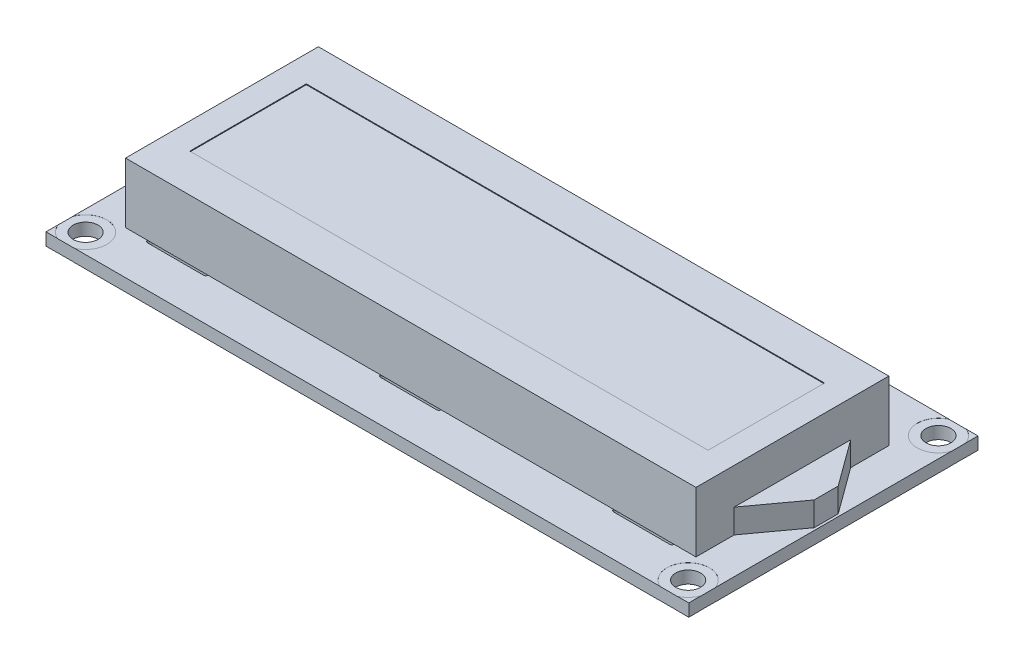
SolidWorks part; units mm, degrees
ref_plane "Front Plane" through (0, 0, 0) normal (0, 0, 1) x (1, 0, 0)
ref_plane "Top Plane" through (0, 0, 0) normal (0, 1, 0) x (1, 0, 0)
ref_plane "Right Plane" through (0, 0, 0) normal (1, 0, 0) x (0, 0, -1)
sketch "Sketch1" plane through (0, 0, 0) normal (0, 1, 0) x (1, 0, 0)
  line L1 (-40, -18) -> (40, -18)
  line L2 (-40, -18) -> (-40, 18)
  line L3 (-40, 18) -> (40, 18)
  line L4 (40, -18) -> (40, 18)
  line L5 (-40, -18) -> (40, 18) construction
  line L6 (-40, 18) -> (40, -18) construction
  point P0 (0, 0)
  dimension "D1" = 36
  dimension "D2" = 80
extrude "PCB" add sketch "Sketch1" along normal blind 1.55
sketch "Sketch2" plane through (0, 1.55, 0) normal (0, 1, 0) x (1, 0, 0)
  line L0 (-42.4796, 0) -> (42.3992, 0) construction
  line L1 (-37.5, 15.575) -> (37.5, 15.575) construction
  circle A0 centre (-37.5, 15.575) radius 1.55
  circle A1 centre (37.5, 15.575) radius 1.55
  circle A2 centre (37.5, -15.575) radius 1.55
  circle A3 centre (-37.5, -15.575) radius 1.55
  circle A4 centre (-37.5, 15.575) radius 2.6 construction
  point P12 (0, 15.575)
  dimension "D1" = 3.1
  dimension "D4" = 5.2
  dimension "D2" = 75
  dimension "D3" = 15.575
extrude "MountingHoles" cut sketch "Sketch2" against normal through all
sketch "Sketch3" plane through (0, 1.55, 0) normal (0, 1, 0) x (1, 0, 0)
  line L0 (0, -21.8483) -> (0, 21.8483) construction
  line L1 (-44.6988, 0) -> (43.4961, 0) construction
  line L2 (40, 18) -> (-40, 18) construction
  line L3 (-32.9, 18) -> (-31.1, 18)
  line L4 (-32.9, 18) -> (-32.9, 16)
  line L5 (-30.36, 18) -> (-30.36, 16)
  line L6 (-31.1, 18) -> (-31.1, 16)
  line L7 (-30.36, 18) -> (-28.56, 18)
  line L8 (-28.56, 18) -> (-28.56, 16)
  line L9 (-27.82, 18) -> (-27.82, 16)
  line L10 (-27.82, 18) -> (-26.02, 18)
  line L11 (-26.02, 18) -> (-26.02, 16)
  line L12 (-25.28, 18) -> (-25.28, 16)
  line L13 (-25.28, 18) -> (-23.48, 18)
  line L14 (-23.48, 18) -> (-23.48, 16)
  line L15 (-22.74, 18) -> (-22.74, 16)
  line L16 (-22.74, 18) -> (-20.94, 18)
  line L17 (-20.94, 18) -> (-20.94, 16)
  line L18 (-20.2, 18) -> (-20.2, 16)
  line L19 (-20.2, 18) -> (-18.4, 18)
  line L20 (-18.4, 18) -> (-18.4, 16)
  line L21 (-17.66, 18) -> (-17.66, 16)
  line L22 (-17.66, 18) -> (-15.86, 18)
  line L23 (-15.86, 18) -> (-15.86, 16)
  line L24 (-15.12, 18) -> (-15.12, 16)
  line L25 (-15.12, 18) -> (-13.32, 18)
  line L26 (-13.32, 18) -> (-13.32, 16)
  line L27 (-12.58, 18) -> (-12.58, 16)
  line L28 (-12.58, 18) -> (-10.78, 18)
  line L29 (-10.78, 18) -> (-10.78, 16)
  line L30 (-10.04, 18) -> (-10.04, 16)
  line L31 (-10.04, 18) -> (-8.24, 18)
  line L32 (-8.24, 18) -> (-8.24, 16)
  line L33 (-7.5, 18) -> (-7.5, 16)
  line L34 (-7.5, 18) -> (-5.7, 18)
  line L35 (-5.7, 18) -> (-5.7, 16)
  line L36 (-4.96, 18) -> (-4.96, 16)
  line L37 (-4.96, 18) -> (-3.16, 18)
  line L38 (-3.16, 18) -> (-3.16, 16)
  line L39 (-2.42, 18) -> (-2.42, 16)
  line L40 (-2.42, 18) -> (-0.62, 18)
  line L41 (-0.62, 18) -> (-0.62, 16)
  line L42 (0.12, 18) -> (0.12, 16)
  line L43 (0.12, 18) -> (1.92, 18)
  line L44 (1.92, 18) -> (1.92, 16)
  line L45 (2.66, 18) -> (2.66, 16)
  line L46 (2.66, 18) -> (4.46, 18)
  line L47 (4.46, 18) -> (4.46, 16)
  line L48 (5.2, 18) -> (5.2, 16)
  line L49 (5.2, 18) -> (7, 18)
  line L50 (7, 18) -> (7, 16)
  circle A0 centre (-37.5, 15.575) radius 2.65
  circle A1 centre (37.5, 15.575) radius 2.65
  circle A2 centre (37.5, -15.575) radius 2.65
  circle A3 centre (-37.5, -15.575) radius 2.65
  arc A4 (-32.9, 16) -> (-31.1, 16) centre (-32, 16) ccw
  arc A5 (-30.36, 16) -> (-28.56, 16) centre (-29.46, 16) ccw
  arc A6 (-27.82, 16) -> (-26.02, 16) centre (-26.92, 16) ccw
  arc A7 (-25.28, 16) -> (-23.48, 16) centre (-24.38, 16) ccw
  arc A8 (-22.74, 16) -> (-20.94, 16) centre (-21.84, 16) ccw
  arc A9 (-20.2, 16) -> (-18.4, 16) centre (-19.3, 16) ccw
  arc A10 (-17.66, 16) -> (-15.86, 16) centre (-16.76, 16) ccw
  arc A11 (-15.12, 16) -> (-13.32, 16) centre (-14.22, 16) ccw
  arc A12 (-12.58, 16) -> (-10.78, 16) centre (-11.68, 16) ccw
  arc A13 (-10.04, 16) -> (-8.24, 16) centre (-9.14, 16) ccw
  arc A14 (-7.5, 16) -> (-5.7, 16) centre (-6.6, 16) ccw
  arc A15 (-4.96, 16) -> (-3.16, 16) centre (-4.06, 16) ccw
  arc A16 (-2.42, 16) -> (-0.62, 16) centre (-1.52, 16) ccw
  arc A17 (0.12, 16) -> (1.92, 16) centre (1.02, 16) ccw
  arc A18 (2.66, 16) -> (4.46, 16) centre (3.56, 16) ccw
  arc A19 (5.2, 16) -> (7, 16) centre (6.1, 16) ccw
  point P21 (0, 0)
  dimension "D1" = 5.3
  dimension "D2" = 1.8
  dimension "D3" = 5.5
  dimension "D4" = 2
  dimension "D6" = 2.54
  dimension "D5" = 16
extrude "Pads" cut sketch "Sketch3" against normal blind 0.01
sketch "Sketch4" plane through (0, 1.55, 0) normal (0, 1, 0) x (1, 0, 0)
  circle A0 centre (-32, 16) radius 0.5
  circle A1 centre (-29.46, 16) radius 0.5
  circle A2 centre (-26.92, 16) radius 0.5
  circle A3 centre (-24.38, 16) radius 0.5
  circle A4 centre (-21.84, 16) radius 0.5
  circle A5 centre (-19.3, 16) radius 0.5
  circle A6 centre (-16.76, 16) radius 0.5
  circle A7 centre (-14.22, 16) radius 0.5
  circle A8 centre (-11.68, 16) radius 0.5
  circle A9 centre (-9.14, 16) radius 0.5
  circle A10 centre (-6.6, 16) radius 0.5
  circle A11 centre (-4.06, 16) radius 0.5
  circle A12 centre (-1.52, 16) radius 0.5
  circle A13 centre (1.02, 16) radius 0.5
  circle A14 centre (3.56, 16) radius 0.5
  circle A15 centre (6.1, 16) radius 0.5
  dimension "D1" = 1
  dimension "D2" = 16
extrude "ConnecterHoles" cut sketch "Sketch4" against normal through all
sketch "Sketch5" plane through (0, 1.55, 0) normal (0, 1, 0) x (1, 0, 0)
  line L0 (36.4314, 18) -> (7, 18) construction
  line L1 (-35.5, -12.6) -> (35.5, -12.6)
  line L2 (-35.5, -12.6) -> (-35.5, 11.4)
  line L3 (-35.5, 11.4) -> (35.5, 11.4)
  line L4 (35.5, -12.6) -> (35.5, 11.4)
  line L5 (-35.5, -12.6) -> (35.5, 11.4) construction
  line L6 (-35.5, 11.4) -> (35.5, -12.6) construction
  point P0 (0, -0.6)
  dimension "D1" = 24
  dimension "D2" = 71
  dimension "D3" = 6.6
extrude "PanelBody" add sketch "Sketch5" along normal blind 7.5
sketch "Sketch6" plane through (0, 9.05, 0) normal (0, 1, 0) x (1, 0, 0)
  line L0 (35.5, -0.6) -> (-35.5, -0.6) construction
  line L1 (-32.25, -7.85) -> (32.25, -7.85)
  line L2 (-32.25, -7.85) -> (-32.25, 6.65)
  line L3 (-32.25, 6.65) -> (32.25, 6.65)
  line L4 (32.25, -7.85) -> (32.25, 6.65)
  line L5 (-32.25, -7.85) -> (32.25, 6.65) construction
  line L6 (-32.25, 6.65) -> (32.25, -7.85) construction
  line L7 (35.5, -12.6) -> (35.5, 11.4) construction
  line L8 (-35.5, 11.4) -> (-35.5, -12.6) construction
  point P0 (0, -0.6)
  dimension "D1" = 14.5
  dimension "D2" = 64.5
extrude "Screen" cut sketch "Sketch6" against normal blind 0.1
sketch "Sketch7" plane through (0, 1.55, 0) normal (0, 1, 0) x (1, 0, 0)
  line L0 (32.5, 11.4) -> (25.5, 11.4) construction
  line L1 (35.5, 11.4) -> (-35.5, 11.4) construction
  line L2 (35.5, 11.4) -> (-35.5, 11.4) construction
  line L3 (32.5, 11.1258) -> (25.5, 11.1258)
  line L4 (32.5, 11.6742) -> (25.5, 11.6742)
  line L5 (35.5, -12.6) -> (35.5, 11.4) construction
  line L6 (0, 21.7861) -> (0, -23.625) construction
  line L7 (-32.5, 11.4) -> (-25.5, 11.4) construction
  line L8 (-32.5, 11.1258) -> (-25.5, 11.1258)
  line L9 (-32.5, 11.6742) -> (-25.5, 11.6742)
  line L10 (-35.5, -0.6) -> (35.5, -0.6) construction
  line L11 (3.5, 11.4) -> (-3.5, 11.4) construction
  line L12 (3.5, 11.1258) -> (-3.5, 11.1258)
  line L13 (3.5, 11.6742) -> (-3.5, 11.6742)
  line L14 (-32.5, 11.4) -> (-25.5, 11.4) construction
  line L15 (-32.5, 11.1258) -> (-25.5, 11.1258)
  line L16 (-32.5, 11.6742) -> (-25.5, 11.6742)
  line L17 (32.5, 11.4) -> (25.5, 11.4) construction
  line L18 (32.5, 11.1258) -> (25.5, 11.1258)
  line L19 (32.5, 11.6742) -> (25.5, 11.6742)
  line L20 (-32.5, 11.4) -> (-25.5, 11.4) construction
  line L21 (-32.5, 11.1258) -> (-25.5, 11.1258)
  line L22 (-32.5, 11.6742) -> (-25.5, 11.6742)
  line L23 (32.5, 11.4) -> (25.5, 11.4) construction
  line L24 (32.5, 11.1258) -> (25.5, 11.1258)
  line L25 (32.5, 11.6742) -> (25.5, 11.6742)
  line L26 (32.5, 11.4) -> (25.5, 11.4) construction
  line L27 (32.5, 11.1258) -> (25.5, 11.1258)
  line L28 (32.5, 11.6742) -> (25.5, 11.6742)
  line L29 (-32.5, 11.4) -> (-25.5, 11.4) construction
  line L30 (-32.5, 11.1258) -> (-25.5, 11.1258)
  line L31 (-32.5, 11.6742) -> (-25.5, 11.6742)
  line L32 (-35.5, 11.4) -> (-35.5, -12.6) construction
  line L33 (-32.5, 11.4) -> (-25.5, 11.4) construction
  line L34 (-32.5, 11.1258) -> (-25.5, 11.1258)
  line L35 (-32.5, 11.6742) -> (-25.5, 11.6742)
  line L36 (32.5, 11.4) -> (25.5, 11.4) construction
  line L37 (32.5, 11.1258) -> (25.5, 11.1258)
  line L38 (32.5, 11.6742) -> (25.5, 11.6742)
  line L39 (32.5, 11.4) -> (25.5, 11.4) construction
  line L40 (32.5, 11.1258) -> (25.5, 11.1258)
  line L41 (32.5, 11.6742) -> (25.5, 11.6742)
  line L42 (-32.5, 11.4) -> (-25.5, 11.4) construction
  line L43 (-32.5, 11.1258) -> (-25.5, 11.1258)
  line L44 (-32.5, 11.6742) -> (-25.5, 11.6742)
  line L45 (32.5, 11.4) -> (25.5, 11.4) construction
  line L46 (32.5, 11.1258) -> (25.5, 11.1258)
  line L47 (32.5, 11.6742) -> (25.5, 11.6742)
  line L48 (-32.5, 11.4) -> (-25.5, 11.4) construction
  line L49 (-32.5, 11.1258) -> (-25.5, 11.1258)
  line L50 (-32.5, 11.6742) -> (-25.5, 11.6742)
  line L51 (-32.5, 11.4) -> (-25.5, 11.4) construction
  line L52 (-32.5, 11.1258) -> (-25.5, 11.1258)
  line L53 (-32.5, 11.6742) -> (-25.5, 11.6742)
  line L54 (32.5, 11.4) -> (25.5, 11.4) construction
  line L55 (32.5, 11.1258) -> (25.5, 11.1258)
  line L56 (32.5, 11.6742) -> (25.5, 11.6742)
  line L57 (-32.5, 11.4) -> (-25.5, 11.4) construction
  line L58 (-32.5, 11.1258) -> (-25.5, 11.1258)
  line L59 (-32.5, 11.6742) -> (-25.5, 11.6742)
  line L60 (32.5, 11.4) -> (25.5, 11.4) construction
  line L61 (32.5, 11.1258) -> (25.5, 11.1258)
  line L62 (32.5, 11.6742) -> (25.5, 11.6742)
  line L63 (32.5, 11.4) -> (25.5, 11.4) construction
  line L64 (32.5, 11.1258) -> (25.5, 11.1258)
  line L65 (32.5, 11.6742) -> (25.5, 11.6742)
  line L66 (-32.5, 11.4) -> (-25.5, 11.4) construction
  line L67 (-32.5, 11.1258) -> (-25.5, 11.1258)
  line L68 (-32.5, 11.6742) -> (-25.5, 11.6742)
  line L69 (32.5, 11.4) -> (25.5, 11.4) construction
  line L70 (32.5, 11.1258) -> (25.5, 11.1258)
  line L71 (32.5, 11.6742) -> (25.5, 11.6742)
  line L72 (-32.5, 11.4) -> (-25.5, 11.4) construction
  line L73 (-32.5, 11.1258) -> (-25.5, 11.1258)
  line L74 (-32.5, 11.6742) -> (-25.5, 11.6742)
  line L75 (-32.5, 11.4) -> (-25.5, 11.4) construction
  line L76 (-32.5, 11.1258) -> (-25.5, 11.1258)
  line L77 (-32.5, 11.6742) -> (-25.5, 11.6742)
  line L78 (32.5, 11.4) -> (25.5, 11.4) construction
  line L79 (32.5, 11.1258) -> (25.5, 11.1258)
  line L80 (32.5, 11.6742) -> (25.5, 11.6742)
  line L81 (32.5, 11.4) -> (25.5, 11.4) construction
  line L82 (32.5, 11.1258) -> (25.5, 11.1258)
  line L83 (32.5, 11.6742) -> (25.5, 11.6742)
  line L84 (-32.5, 11.4) -> (-25.5, 11.4) construction
  line L85 (-32.5, 11.1258) -> (-25.5, 11.1258)
  line L86 (-32.5, 11.6742) -> (-25.5, 11.6742)
  line L87 (-32.5, 11.4) -> (-25.5, 11.4) construction
  line L88 (-32.5, 11.1258) -> (-25.5, 11.1258)
  line L89 (-32.5, 11.6742) -> (-25.5, 11.6742)
  line L90 (32.5, 11.4) -> (25.5, 11.4) construction
  line L91 (32.5, 11.1258) -> (25.5, 11.1258)
  line L92 (32.5, 11.6742) -> (25.5, 11.6742)
  line L93 (-32.5, 11.4) -> (-25.5, 11.4) construction
  line L94 (-32.5, 11.1258) -> (-25.5, 11.1258)
  line L95 (-32.5, 11.6742) -> (-25.5, 11.6742)
  line L96 (32.5, 11.4) -> (25.5, 11.4) construction
  line L97 (32.5, 11.1258) -> (25.5, 11.1258)
  line L98 (32.5, 11.6742) -> (25.5, 11.6742)
  line L99 (32.5, 11.4) -> (25.5, 11.4) construction
  line L100 (32.5, 11.1258) -> (25.5, 11.1258)
  line L101 (32.5, 11.6742) -> (25.5, 11.6742)
  line L102 (-32.5, 11.4) -> (-25.5, 11.4) construction
  line L103 (-32.5, 11.1258) -> (-25.5, 11.1258)
  line L104 (-32.5, 11.6742) -> (-25.5, 11.6742)
  line L105 (32.5, -12.6) -> (25.5, -12.6) construction
  line L106 (32.5, -12.3258) -> (25.5, -12.3258)
  line L107 (32.5, -12.8742) -> (25.5, -12.8742)
  line L108 (-32.5, -12.6) -> (-25.5, -12.6) construction
  line L109 (-32.5, -12.3258) -> (-25.5, -12.3258)
  line L110 (-32.5, -12.8742) -> (-25.5, -12.8742)
  line L111 (32.5, -12.6) -> (25.5, -12.6) construction
  line L112 (32.5, -12.3258) -> (25.5, -12.3258)
  line L113 (32.5, -12.8742) -> (25.5, -12.8742)
  line L114 (-32.5, -12.6) -> (-25.5, -12.6) construction
  line L115 (-32.5, -12.3258) -> (-25.5, -12.3258)
  line L116 (-32.5, -12.8742) -> (-25.5, -12.8742)
  line L117 (-32.5, -12.6) -> (-25.5, -12.6) construction
  line L118 (-32.5, -12.3258) -> (-25.5, -12.3258)
  line L119 (-32.5, -12.8742) -> (-25.5, -12.8742)
  line L120 (32.5, -12.6) -> (25.5, -12.6) construction
  line L121 (32.5, -12.3258) -> (25.5, -12.3258)
  line L122 (32.5, -12.8742) -> (25.5, -12.8742)
  line L123 (32.5, -12.6) -> (25.5, -12.6) construction
  line L124 (32.5, -12.3258) -> (25.5, -12.3258)
  line L125 (32.5, -12.8742) -> (25.5, -12.8742)
  line L126 (-32.5, -12.6) -> (-25.5, -12.6) construction
  line L127 (-32.5, -12.3258) -> (-25.5, -12.3258)
  line L128 (-32.5, -12.8742) -> (-25.5, -12.8742)
  line L129 (-32.5, -12.6) -> (-25.5, -12.6) construction
  line L130 (-32.5, -12.3258) -> (-25.5, -12.3258)
  line L131 (-32.5, -12.8742) -> (-25.5, -12.8742)
  line L132 (32.5, -12.6) -> (25.5, -12.6) construction
  line L133 (32.5, -12.3258) -> (25.5, -12.3258)
  line L134 (32.5, -12.8742) -> (25.5, -12.8742)
  line L135 (-32.5, -12.6) -> (-25.5, -12.6) construction
  line L136 (-32.5, -12.3258) -> (-25.5, -12.3258)
  line L137 (-32.5, -12.8742) -> (-25.5, -12.8742)
  line L138 (32.5, -12.6) -> (25.5, -12.6) construction
  line L139 (32.5, -12.3258) -> (25.5, -12.3258)
  line L140 (32.5, -12.8742) -> (25.5, -12.8742)
  line L141 (32.5, -12.6) -> (25.5, -12.6) construction
  line L142 (32.5, -12.3258) -> (25.5, -12.3258)
  line L143 (32.5, -12.8742) -> (25.5, -12.8742)
  line L144 (-32.5, -12.6) -> (-25.5, -12.6) construction
  line L145 (-32.5, -12.3258) -> (-25.5, -12.3258)
  line L146 (-32.5, -12.8742) -> (-25.5, -12.8742)
  line L147 (32.5, -12.6) -> (25.5, -12.6) construction
  line L148 (32.5, -12.3258) -> (25.5, -12.3258)
  line L149 (32.5, -12.8742) -> (25.5, -12.8742)
  line L150 (-32.5, -12.6) -> (-25.5, -12.6) construction
  line L151 (-32.5, -12.3258) -> (-25.5, -12.3258)
  line L152 (-32.5, -12.8742) -> (-25.5, -12.8742)
  line L153 (-32.5, -12.6) -> (-25.5, -12.6) construction
  line L154 (-32.5, -12.3258) -> (-25.5, -12.3258)
  line L155 (-32.5, -12.8742) -> (-25.5, -12.8742)
  line L156 (32.5, -12.6) -> (25.5, -12.6) construction
  line L157 (32.5, -12.3258) -> (25.5, -12.3258)
  line L158 (32.5, -12.8742) -> (25.5, -12.8742)
  line L159 (-32.5, -12.6) -> (-25.5, -12.6) construction
  line L160 (-32.5, -12.3258) -> (-25.5, -12.3258)
  line L161 (-32.5, -12.8742) -> (-25.5, -12.8742)
  line L162 (32.5, -12.6) -> (25.5, -12.6) construction
  line L163 (32.5, -12.3258) -> (25.5, -12.3258)
  line L164 (32.5, -12.8742) -> (25.5, -12.8742)
  line L165 (32.5, -12.6) -> (25.5, -12.6) construction
  line L166 (32.5, -12.3258) -> (25.5, -12.3258)
  line L167 (32.5, -12.8742) -> (25.5, -12.8742)
  line L168 (-32.5, -12.6) -> (-25.5, -12.6) construction
  line L169 (-32.5, -12.3258) -> (-25.5, -12.3258)
  line L170 (-32.5, -12.8742) -> (-25.5, -12.8742)
  line L171 (-32.5, -12.6) -> (-25.5, -12.6) construction
  line L172 (-32.5, -12.3258) -> (-25.5, -12.3258)
  line L173 (-32.5, -12.8742) -> (-25.5, -12.8742)
  line L174 (32.5, -12.6) -> (25.5, -12.6) construction
  line L175 (32.5, -12.3258) -> (25.5, -12.3258)
  line L176 (32.5, -12.8742) -> (25.5, -12.8742)
  line L177 (32.5, -12.6) -> (25.5, -12.6) construction
  line L178 (32.5, -12.3258) -> (25.5, -12.3258)
  line L179 (32.5, -12.8742) -> (25.5, -12.8742)
  line L180 (-32.5, -12.6) -> (-25.5, -12.6) construction
  line L181 (-32.5, -12.3258) -> (-25.5, -12.3258)
  line L182 (-32.5, -12.8742) -> (-25.5, -12.8742)
  line L183 (32.5, -12.6) -> (25.5, -12.6) construction
  line L184 (32.5, -12.3258) -> (25.5, -12.3258)
  line L185 (32.5, -12.8742) -> (25.5, -12.8742)
  line L186 (-32.5, -12.6) -> (-25.5, -12.6) construction
  line L187 (-32.5, -12.3258) -> (-25.5, -12.3258)
  line L188 (-32.5, -12.8742) -> (-25.5, -12.8742)
  line L189 (-32.5, -12.6) -> (-25.5, -12.6) construction
  line L190 (-32.5, -12.3258) -> (-25.5, -12.3258)
  line L191 (-32.5, -12.8742) -> (-25.5, -12.8742)
  line L192 (32.5, -12.6) -> (25.5, -12.6) construction
  line L193 (32.5, -12.3258) -> (25.5, -12.3258)
  line L194 (32.5, -12.8742) -> (25.5, -12.8742)
  line L195 (3.5, -12.6) -> (-3.5, -12.6) construction
  line L196 (3.5, -12.3258) -> (-3.5, -12.3258)
  line L197 (3.5, -12.8742) -> (-3.5, -12.8742)
  line L198 (-32.5, -12.6) -> (-25.5, -12.6) construction
  line L199 (-32.5, -12.3258) -> (-25.5, -12.3258)
  line L200 (-32.5, -12.8742) -> (-25.5, -12.8742)
  line L201 (32.5, -12.6) -> (25.5, -12.6) construction
  line L202 (32.5, -12.3258) -> (25.5, -12.3258)
  line L203 (32.5, -12.8742) -> (25.5, -12.8742)
  arc A0 (32.5, 11.1258) -> (32.5, 11.6742) centre (32.5, 11.4) ccw
  arc A1 (25.5, 11.6742) -> (25.5, 11.1258) centre (25.5, 11.4) ccw
  arc A2 (-32.5, 11.1258) -> (-32.5, 11.6742) centre (-32.5, 11.4) cw
  arc A3 (-25.5, 11.6742) -> (-25.5, 11.1258) centre (-25.5, 11.4) cw
  arc A4 (3.5, 11.1258) -> (3.5, 11.6742) centre (3.5, 11.4) ccw
  arc A5 (-3.5, 11.6742) -> (-3.5, 11.1258) centre (-3.5, 11.4) ccw
  arc A6 (-32.5, 11.1258) -> (-32.5, 11.6742) centre (-32.5, 11.4) cw
  arc A7 (-25.5, 11.6742) -> (-25.5, 11.1258) centre (-25.5, 11.4) cw
  arc A8 (32.5, 11.1258) -> (32.5, 11.6742) centre (32.5, 11.4) ccw
  arc A9 (25.5, 11.6742) -> (25.5, 11.1258) centre (25.5, 11.4) ccw
  arc A10 (-32.5, 11.1258) -> (-32.5, 11.6742) centre (-32.5, 11.4) cw
  arc A11 (-25.5, 11.6742) -> (-25.5, 11.1258) centre (-25.5, 11.4) cw
  arc A12 (32.5, 11.1258) -> (32.5, 11.6742) centre (32.5, 11.4) ccw
  arc A13 (25.5, 11.6742) -> (25.5, 11.1258) centre (25.5, 11.4) ccw
  arc A14 (32.5, 11.1258) -> (32.5, 11.6742) centre (32.5, 11.4) ccw
  arc A15 (25.5, 11.6742) -> (25.5, 11.1258) centre (25.5, 11.4) ccw
  arc A16 (-32.5, 11.1258) -> (-32.5, 11.6742) centre (-32.5, 11.4) cw
  arc A17 (-25.5, 11.6742) -> (-25.5, 11.1258) centre (-25.5, 11.4) cw
  arc A18 (-32.5, 11.1258) -> (-32.5, 11.6742) centre (-32.5, 11.4) cw
  arc A19 (-25.5, 11.6742) -> (-25.5, 11.1258) centre (-25.5, 11.4) cw
  arc A20 (32.5, 11.1258) -> (32.5, 11.6742) centre (32.5, 11.4) ccw
  arc A21 (25.5, 11.6742) -> (25.5, 11.1258) centre (25.5, 11.4) ccw
  arc A22 (32.5, 11.1258) -> (32.5, 11.6742) centre (32.5, 11.4) ccw
  arc A23 (25.5, 11.6742) -> (25.5, 11.1258) centre (25.5, 11.4) ccw
  arc A24 (-32.5, 11.1258) -> (-32.5, 11.6742) centre (-32.5, 11.4) cw
  arc A25 (-25.5, 11.6742) -> (-25.5, 11.1258) centre (-25.5, 11.4) cw
  arc A26 (32.5, 11.1258) -> (32.5, 11.6742) centre (32.5, 11.4) ccw
  arc A27 (25.5, 11.6742) -> (25.5, 11.1258) centre (25.5, 11.4) ccw
  arc A28 (-32.5, 11.1258) -> (-32.5, 11.6742) centre (-32.5, 11.4) cw
  arc A29 (-25.5, 11.6742) -> (-25.5, 11.1258) centre (-25.5, 11.4) cw
  arc A30 (-32.5, 11.1258) -> (-32.5, 11.6742) centre (-32.5, 11.4) cw
  arc A31 (-25.5, 11.6742) -> (-25.5, 11.1258) centre (-25.5, 11.4) cw
  arc A32 (32.5, 11.1258) -> (32.5, 11.6742) centre (32.5, 11.4) ccw
  arc A33 (25.5, 11.6742) -> (25.5, 11.1258) centre (25.5, 11.4) ccw
  arc A34 (-32.5, 11.1258) -> (-32.5, 11.6742) centre (-32.5, 11.4) cw
  arc A35 (-25.5, 11.6742) -> (-25.5, 11.1258) centre (-25.5, 11.4) cw
  arc A36 (32.5, 11.1258) -> (32.5, 11.6742) centre (32.5, 11.4) ccw
  arc A37 (25.5, 11.6742) -> (25.5, 11.1258) centre (25.5, 11.4) ccw
  arc A38 (32.5, 11.1258) -> (32.5, 11.6742) centre (32.5, 11.4) ccw
  arc A39 (25.5, 11.6742) -> (25.5, 11.1258) centre (25.5, 11.4) ccw
  arc A40 (-32.5, 11.1258) -> (-32.5, 11.6742) centre (-32.5, 11.4) cw
  arc A41 (-25.5, 11.6742) -> (-25.5, 11.1258) centre (-25.5, 11.4) cw
  arc A42 (32.5, 11.1258) -> (32.5, 11.6742) centre (32.5, 11.4) ccw
  arc A43 (25.5, 11.6742) -> (25.5, 11.1258) centre (25.5, 11.4) ccw
  arc A44 (-32.5, 11.1258) -> (-32.5, 11.6742) centre (-32.5, 11.4) cw
  arc A45 (-25.5, 11.6742) -> (-25.5, 11.1258) centre (-25.5, 11.4) cw
  arc A46 (-32.5, 11.1258) -> (-32.5, 11.6742) centre (-32.5, 11.4) cw
  arc A47 (-25.5, 11.6742) -> (-25.5, 11.1258) centre (-25.5, 11.4) cw
  arc A48 (32.5, 11.1258) -> (32.5, 11.6742) centre (32.5, 11.4) ccw
  arc A49 (25.5, 11.6742) -> (25.5, 11.1258) centre (25.5, 11.4) ccw
  arc A50 (32.5, 11.1258) -> (32.5, 11.6742) centre (32.5, 11.4) ccw
  arc A51 (25.5, 11.6742) -> (25.5, 11.1258) centre (25.5, 11.4) ccw
  arc A52 (-32.5, 11.1258) -> (-32.5, 11.6742) centre (-32.5, 11.4) cw
  arc A53 (-25.5, 11.6742) -> (-25.5, 11.1258) centre (-25.5, 11.4) cw
  arc A54 (-32.5, 11.1258) -> (-32.5, 11.6742) centre (-32.5, 11.4) cw
  arc A55 (-25.5, 11.6742) -> (-25.5, 11.1258) centre (-25.5, 11.4) cw
  arc A56 (32.5, 11.1258) -> (32.5, 11.6742) centre (32.5, 11.4) ccw
  arc A57 (25.5, 11.6742) -> (25.5, 11.1258) centre (25.5, 11.4) ccw
  arc A58 (-32.5, 11.1258) -> (-32.5, 11.6742) centre (-32.5, 11.4) cw
  arc A59 (-25.5, 11.6742) -> (-25.5, 11.1258) centre (-25.5, 11.4) cw
  arc A60 (32.5, 11.1258) -> (32.5, 11.6742) centre (32.5, 11.4) ccw
  arc A61 (25.5, 11.6742) -> (25.5, 11.1258) centre (25.5, 11.4) ccw
  arc A62 (32.5, 11.1258) -> (32.5, 11.6742) centre (32.5, 11.4) ccw
  arc A63 (25.5, 11.6742) -> (25.5, 11.1258) centre (25.5, 11.4) ccw
  arc A64 (-32.5, 11.1258) -> (-32.5, 11.6742) centre (-32.5, 11.4) cw
  arc A65 (-25.5, 11.6742) -> (-25.5, 11.1258) centre (-25.5, 11.4) cw
  arc A66 (32.5, -12.3258) -> (32.5, -12.8742) centre (32.5, -12.6) cw
  arc A67 (25.5, -12.8742) -> (25.5, -12.3258) centre (25.5, -12.6) cw
  arc A68 (-32.5, -12.3258) -> (-32.5, -12.8742) centre (-32.5, -12.6) ccw
  arc A69 (-25.5, -12.8742) -> (-25.5, -12.3258) centre (-25.5, -12.6) ccw
  arc A70 (32.5, -12.3258) -> (32.5, -12.8742) centre (32.5, -12.6) cw
  arc A71 (25.5, -12.8742) -> (25.5, -12.3258) centre (25.5, -12.6) cw
  arc A72 (-32.5, -12.3258) -> (-32.5, -12.8742) centre (-32.5, -12.6) ccw
  arc A73 (-25.5, -12.8742) -> (-25.5, -12.3258) centre (-25.5, -12.6) ccw
  arc A74 (-32.5, -12.3258) -> (-32.5, -12.8742) centre (-32.5, -12.6) ccw
  arc A75 (-25.5, -12.8742) -> (-25.5, -12.3258) centre (-25.5, -12.6) ccw
  arc A76 (32.5, -12.3258) -> (32.5, -12.8742) centre (32.5, -12.6) cw
  arc A77 (25.5, -12.8742) -> (25.5, -12.3258) centre (25.5, -12.6) cw
  arc A78 (32.5, -12.3258) -> (32.5, -12.8742) centre (32.5, -12.6) cw
  arc A79 (25.5, -12.8742) -> (25.5, -12.3258) centre (25.5, -12.6) cw
  arc A80 (-32.5, -12.3258) -> (-32.5, -12.8742) centre (-32.5, -12.6) ccw
  arc A81 (-25.5, -12.8742) -> (-25.5, -12.3258) centre (-25.5, -12.6) ccw
  arc A82 (-32.5, -12.3258) -> (-32.5, -12.8742) centre (-32.5, -12.6) ccw
  arc A83 (-25.5, -12.8742) -> (-25.5, -12.3258) centre (-25.5, -12.6) ccw
  arc A84 (32.5, -12.3258) -> (32.5, -12.8742) centre (32.5, -12.6) cw
  arc A85 (25.5, -12.8742) -> (25.5, -12.3258) centre (25.5, -12.6) cw
  arc A86 (-32.5, -12.3258) -> (-32.5, -12.8742) centre (-32.5, -12.6) ccw
  arc A87 (-25.5, -12.8742) -> (-25.5, -12.3258) centre (-25.5, -12.6) ccw
  arc A88 (32.5, -12.3258) -> (32.5, -12.8742) centre (32.5, -12.6) cw
  arc A89 (25.5, -12.8742) -> (25.5, -12.3258) centre (25.5, -12.6) cw
  arc A90 (32.5, -12.3258) -> (32.5, -12.8742) centre (32.5, -12.6) cw
  arc A91 (25.5, -12.8742) -> (25.5, -12.3258) centre (25.5, -12.6) cw
  arc A92 (-32.5, -12.3258) -> (-32.5, -12.8742) centre (-32.5, -12.6) ccw
  arc A93 (-25.5, -12.8742) -> (-25.5, -12.3258) centre (-25.5, -12.6) ccw
  arc A94 (32.5, -12.3258) -> (32.5, -12.8742) centre (32.5, -12.6) cw
  arc A95 (25.5, -12.8742) -> (25.5, -12.3258) centre (25.5, -12.6) cw
  arc A96 (-32.5, -12.3258) -> (-32.5, -12.8742) centre (-32.5, -12.6) ccw
  arc A97 (-25.5, -12.8742) -> (-25.5, -12.3258) centre (-25.5, -12.6) ccw
  arc A98 (-32.5, -12.3258) -> (-32.5, -12.8742) centre (-32.5, -12.6) ccw
  arc A99 (-25.5, -12.8742) -> (-25.5, -12.3258) centre (-25.5, -12.6) ccw
  arc A100 (32.5, -12.3258) -> (32.5, -12.8742) centre (32.5, -12.6) cw
  arc A101 (25.5, -12.8742) -> (25.5, -12.3258) centre (25.5, -12.6) cw
  arc A102 (-32.5, -12.3258) -> (-32.5, -12.8742) centre (-32.5, -12.6) ccw
  arc A103 (-25.5, -12.8742) -> (-25.5, -12.3258) centre (-25.5, -12.6) ccw
  arc A104 (32.5, -12.3258) -> (32.5, -12.8742) centre (32.5, -12.6) cw
  arc A105 (25.5, -12.8742) -> (25.5, -12.3258) centre (25.5, -12.6) cw
  arc A106 (32.5, -12.3258) -> (32.5, -12.8742) centre (32.5, -12.6) cw
  arc A107 (25.5, -12.8742) -> (25.5, -12.3258) centre (25.5, -12.6) cw
  arc A108 (-32.5, -12.3258) -> (-32.5, -12.8742) centre (-32.5, -12.6) ccw
  arc A109 (-25.5, -12.8742) -> (-25.5, -12.3258) centre (-25.5, -12.6) ccw
  arc A110 (-32.5, -12.3258) -> (-32.5, -12.8742) centre (-32.5, -12.6) ccw
  arc A111 (-25.5, -12.8742) -> (-25.5, -12.3258) centre (-25.5, -12.6) ccw
  arc A112 (32.5, -12.3258) -> (32.5, -12.8742) centre (32.5, -12.6) cw
  arc A113 (25.5, -12.8742) -> (25.5, -12.3258) centre (25.5, -12.6) cw
  arc A114 (32.5, -12.3258) -> (32.5, -12.8742) centre (32.5, -12.6) cw
  arc A115 (25.5, -12.8742) -> (25.5, -12.3258) centre (25.5, -12.6) cw
  arc A116 (-32.5, -12.3258) -> (-32.5, -12.8742) centre (-32.5, -12.6) ccw
  arc A117 (-25.5, -12.8742) -> (-25.5, -12.3258) centre (-25.5, -12.6) ccw
  arc A118 (32.5, -12.3258) -> (32.5, -12.8742) centre (32.5, -12.6) cw
  arc A119 (25.5, -12.8742) -> (25.5, -12.3258) centre (25.5, -12.6) cw
  arc A120 (-32.5, -12.3258) -> (-32.5, -12.8742) centre (-32.5, -12.6) ccw
  arc A121 (-25.5, -12.8742) -> (-25.5, -12.3258) centre (-25.5, -12.6) ccw
  arc A122 (-32.5, -12.3258) -> (-32.5, -12.8742) centre (-32.5, -12.6) ccw
  arc A123 (-25.5, -12.8742) -> (-25.5, -12.3258) centre (-25.5, -12.6) ccw
  arc A124 (32.5, -12.3258) -> (32.5, -12.8742) centre (32.5, -12.6) cw
  arc A125 (25.5, -12.8742) -> (25.5, -12.3258) centre (25.5, -12.6) cw
  arc A126 (3.5, -12.3258) -> (3.5, -12.8742) centre (3.5, -12.6) cw
  arc A127 (-3.5, -12.8742) -> (-3.5, -12.3258) centre (-3.5, -12.6) cw
  arc A128 (-32.5, -12.3258) -> (-32.5, -12.8742) centre (-32.5, -12.6) ccw
  arc A129 (-25.5, -12.8742) -> (-25.5, -12.3258) centre (-25.5, -12.6) ccw
  arc A130 (32.5, -12.3258) -> (32.5, -12.8742) centre (32.5, -12.6) cw
  arc A131 (25.5, -12.8742) -> (25.5, -12.3258) centre (25.5, -12.6) cw
  point P6 (29, 11.4)
  point P18 (-29, 11.4)
  point P27 (0, 11.4)
  point P216 (29, -12.6)
  point P223 (-29, -12.6)
  point P398 (0, -12.6)
  dimension "D1" = 7
  dimension "D2" = 6.5
  dimension "D3" = 7
extrude "PanelMountHoles" cut sketch "Sketch7" against normal through all contours L13 A5 L12 A4 | L4 A1 L3 A0 | L106 A67 L107 A66 | L196 A127 L197 A126 | L109 A69 L110 A68 | L9 A3 L8 A2
sketch "Sketch8" plane through (0, 0, 0) normal (0, -1, 0) x (1, 0, 0)
  line L0 (32.5, 12.3258) -> (26.1128, 9.2992)
  line L1 (26.1128, 9.2992) -> (26.0208, 9.4935)
  line L2 (26.0208, 9.4935) -> (32.4079, 12.52)
  line L3 (32.5, 12.3258) -> (32.4079, 12.52)
  line L4 (32.0883, -8.3386) -> (25.7012, -11.3651)
  line L5 (25.7012, -11.3651) -> (25.6091, -11.1709)
  line L6 (25.6091, -11.1709) -> (31.9963, -8.1443)
  line L7 (32.0883, -8.3386) -> (31.9963, -8.1443)
  line L8 (3.5, 12.3258) -> (-2.8872, 9.2992)
  line L9 (-2.8872, 9.2992) -> (-2.9792, 9.4935)
  line L10 (-2.9792, 9.4935) -> (3.4079, 12.52)
  line L11 (3.5, 12.3258) -> (3.4079, 12.52)
  line L12 (3.0883, -8.3386) -> (-3.2988, -11.3651)
  line L13 (-3.2988, -11.3651) -> (-3.3909, -11.1709)
  line L14 (-3.3909, -11.1709) -> (2.9963, -8.1443)
  line L15 (3.0883, -8.3386) -> (2.9963, -8.1443)
  line L16 (-25.5, 12.3258) -> (-31.8872, 9.2992)
  line L17 (-31.8872, 9.2992) -> (-31.9792, 9.4935)
  line L18 (-31.9792, 9.4935) -> (-25.5921, 12.52)
  line L19 (-25.5, 12.3258) -> (-25.5921, 12.52)
  line L20 (-25.9117, -8.3386) -> (-32.2988, -11.3651)
  line L21 (-32.2988, -11.3651) -> (-32.3909, -11.1709)
  line L22 (-32.3909, -11.1709) -> (-26.0037, -8.1443)
  line L23 (-25.9117, -8.3386) -> (-26.0037, -8.1443)
  dimension "D1" = 3
extrude "PanelMounts" add sketch "Sketch8" along normal blind 2.5
sketch "Sketch9" plane through (0, 1.55, 0) normal (0, 1, 0) x (1, 0, 0)
  line L0 (35.5, -7.85) -> (35.5, 6.65)
  line L2 (35.5, -12.6) -> (35.5, 11.4) construction
  line L3 (35.5, 6.65) -> (39.7, 0.9)
  line L4 (39.7, 0.9) -> (39.7, -2.1)
  line L5 (39.7, -2.1) -> (35.5, -7.85)
  line L6 (40, -14.6961) -> (40, 14.6961) construction
  point P0 (35.5, -0.6)
  point P3 (35.5, -0.6)
  point P4 (39.7, -0.6)
  dimension "D1" = 14.5
  dimension "D2" = 3
  dimension "D3" = 0.3
extrude "WhiteThing" add sketch "Sketch9" along normal blind 3
ref_plane "MidPCB" through (0, 0.775, 0) normal (0, 1, 0) x (1, 0, 0)
mirror "BackSidePads" about plane through (0, 0.775, 0) normal (0, 1, 0) of "Pads"
